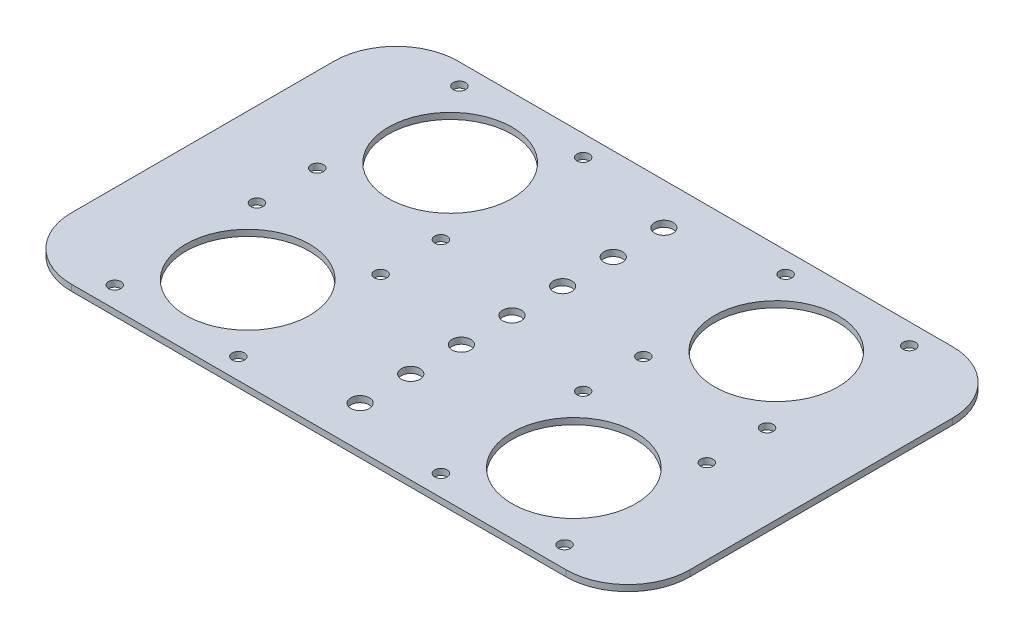
SolidWorks part; units mm, degrees
material "3.3523 (EN-AW 5052)"
ref_plane "Спереди" through (0, 0, 0) normal (0, 0, 1) x (1, 0, 0)
ref_plane "Сверху" through (0, 0, 0) normal (0, 1, 0) x (1, 0, 0)
ref_plane "Справа" through (0, 0, 0) normal (1, 0, 0) x (0, 0, -1)
sketch "Эскиз1" plane through (0, 0, 0) normal (0, 1, 0) x (1, 0, 0)
  line L1 (0, 0) -> (200, 0)
  line L2 (0, 0) -> (0, 125)
  line L3 (0, 125) -> (200, 125)
  line L4 (200, 0) -> (200, 125)
  dimension "D1" = 200
  dimension "D2" = 125
extrude "Бобышка-Вытянуть1" add sketch "Эскиз1" along normal blind 2
sketch "Эскиз2" plane through (0, 0, 0) normal (0, -1, 0) x (1, 0, 0)
  circle A0 centre (27.25, -6.75) radius 2
  circle A1 centre (67.25, -6.75) radius 2
  circle A2 centre (132.75, -6.75) radius 2
  circle A3 centre (172.75, -6.75) radius 2
  circle A4 centre (172.75, -52.75) radius 2
  circle A5 centre (132.75, -52.75) radius 2
  circle A6 centre (132.75, -72.25) radius 2
  circle A7 centre (172.75, -72.25) radius 2
  circle A8 centre (132.75, -118.25) radius 2
  circle A9 centre (172.75, -118.25) radius 2
  circle A10 centre (27.25, -52.75) radius 2
  circle A11 centre (67.25, -52.75) radius 2
  circle A12 centre (27.25, -72.25) radius 2
  circle A13 centre (67.25, -72.25) radius 2
  circle A14 centre (67.25, -118.25) radius 2
  circle A15 centre (27.25, -118.25) radius 2
extrude "Вырез-Вытянуть1" cut sketch "Эскиз2" against normal through all
sketch "Эскиз3" plane through (0, 0, 0) normal (0, -1, 0) x (1, 0, 0)
  line L0 (27.25, -6.75) -> (67.25, -52.75) construction
  line L1 (67.25, -52.75) -> (67.25, -72.25) construction
  line L2 (67.25, -72.25) -> (27.25, -118.25) construction
  line L3 (27.25, -118.25) -> (132.75, -118.25) construction
  line L4 (132.75, -118.25) -> (172.75, -72.25) construction
  line L5 (172.75, -72.25) -> (172.75, -52.75) construction
  line L6 (172.75, -52.75) -> (132.75, -6.75) construction
  line L7 (100, 0) -> (100, -26.75) construction
  line L8 (0, 0) -> (200, 0) construction
  line L9 (200, -125) -> (0, -125) construction
  line L10 (100, -65.5) -> (100, -92.25) construction
  line L11 (100, -32.75) -> (100, -59.5) construction
  line L12 (100, -98.25) -> (100, -125) construction
  circle A0 centre (47.25, -29.75) radius 20
  circle A1 centre (152.75, -29.75) radius 20
  circle A2 centre (152.75, -95.25) radius 20
  circle A3 centre (47.25, -95.25) radius 20
  circle A4 centre (100, -62.5) radius 3
  circle A5 centre (100, -29.75) radius 3
  circle A6 centre (100, -95.25) radius 3
  circle A7 centre (100, -13.375) radius 3
  circle A8 centre (100, -46.125) radius 3
  circle A9 centre (100, -78.875) radius 3
  circle A10 centre (100, -111.625) radius 3
extrude "Вырез-Вытянуть2" cut sketch "Эскиз3" against normal through all
fillet "Скругление1" radius 20 4 edges at (200, 1, -125) (0, 1, -125) (0, 1, 0) (200, 1, 0)
